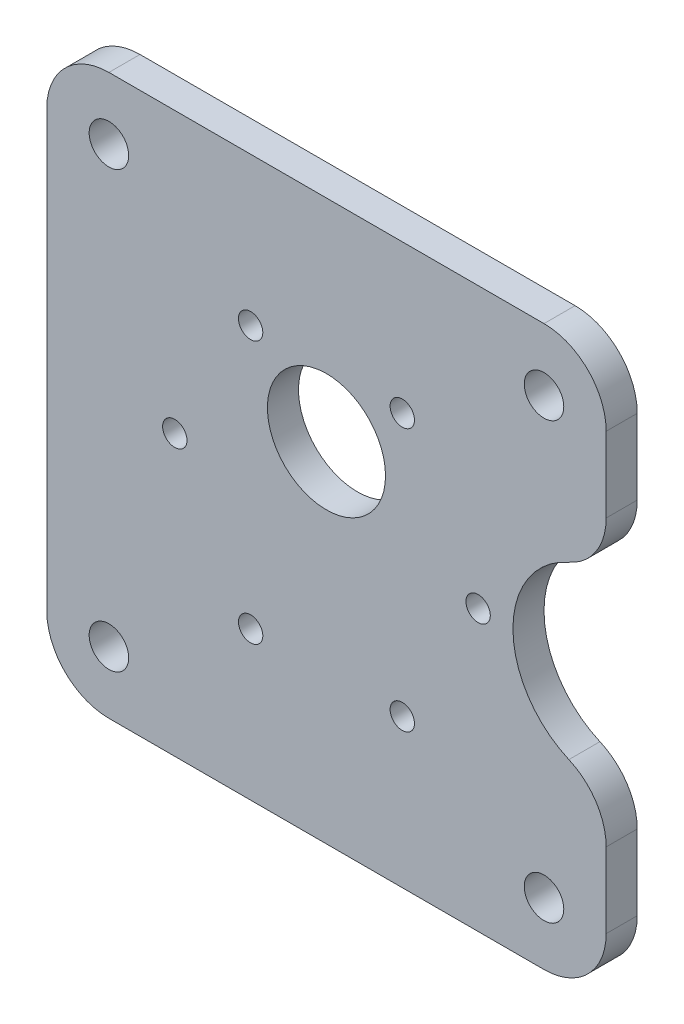
SolidWorks part; units mm, degrees
material "6061 Alloy"
ref_plane "Front Plane" through (0, 0, 0) normal (0, 0, 1) x (1, 0, 0)
ref_plane "Top Plane" through (0, 0, 0) normal (0, 1, 0) x (1, 0, 0)
ref_plane "Right Plane" through (0, 0, 0) normal (1, 0, 0) x (0, 0, -1)
sketch "Sketch1" plane through (0, 0, 0) normal (0, 0, 1) x (1, 0, 0)
  line L0 (0, 0) -> (-15.494, 0) construction
  line L1 (0, 0) -> (-7.747, 13.4182) construction
  line L3 (-28.575, 28.575) -> (28.575, 28.575)
  line L4 (-28.575, 28.575) -> (-28.575, -28.575)
  line L5 (-28.575, -28.575) -> (28.575, -28.575)
  line L6 (28.575, 28.575) -> (28.575, -28.575)
  line L7 (-28.575, 28.575) -> (28.575, -28.575) construction
  line L8 (-28.575, -28.575) -> (28.575, 28.575) construction
  line L9 (22.225, -22.225) -> (-22.225, -22.225) construction
  line L10 (22.225, -22.225) -> (22.225, 22.225) construction
  line L11 (22.225, 22.225) -> (-22.225, 22.225) construction
  line L12 (-22.225, -22.225) -> (-22.225, 22.225) construction
  line L13 (22.225, -22.225) -> (-22.225, 22.225) construction
  line L14 (22.225, 22.225) -> (-22.225, -22.225) construction
  circle A0 centre (0, 0) radius 15.494 construction
  circle A1 centre (-15.494, 0) radius 1.2446
  circle A2 centre (-7.747, 13.4182) radius 1.2446
  circle A3 centre (7.747, 13.4182) radius 1.2446
  circle A4 centre (15.494, 0) radius 1.2446
  circle A5 centre (7.747, -13.4182) radius 1.2446
  circle A6 centre (-7.747, -13.4182) radius 1.2446
  circle A7 centre (0, 7.0104) radius 6.0325
  circle A8 centre (-22.225, 22.225) radius 6.35 construction
  circle A9 centre (-22.225, -22.225) radius 6.35 construction
  circle A10 centre (22.225, -22.225) radius 6.35 construction
  circle A11 centre (22.225, 22.225) radius 6.35 construction
  circle A12 centre (-22.225, 22.225) radius 2.0193
  circle A13 centre (22.225, 22.225) radius 2.0193
  circle A14 centre (-22.225, -22.225) radius 2.0193
  circle A15 centre (22.225, -22.225) radius 2.0193
  arc A16 (28.575, 9.525) -> (28.575, -9.525) centre (28.575, 0) ccw
  point P38 (28.575, 0)
  dimension "D1" = 30.988
  dimension "D2" = 2.4892
  dimension "D3" = 6
  dimension "D4" = 60
  dimension "D6" = 12.065
  dimension "D10" = 12.7
  dimension "D11" = 4.0386
  dimension "D12" = 9.525
  dimension "D5" = 15.494
  dimension "D7" = 7.0104
  dimension "D8" = 57.15
  dimension "D9" = 57.15
extrude "Boss-Extrude1" add sketch "Sketch1" along normal mid plane 3.175
fillet "Fillet2" radius 6.35 6 edges at (-28.575, -28.575, 0) (28.575, -28.575, 0) (28.575, 28.575, 0) (-28.575, 28.575, 0) (28.575, 9.525, 0) (28.575, -9.525, 0)
sketch "Sketch2" plane through (0, 0, 1.5875) normal (0, 0, 1) x (1, 0, 0)
  line L0 (-1000, -28.575) -> (49000, -28.575) construction
  line L1 (-22.225, -28.575) -> (22.225, -28.575) construction
  line L2 (28.575, -981.6127) -> (28.575, 49018.3873) construction
  line L3 (28.575, 22.225) -> (28.575, 14.5497) construction
  line L4 (-1001.131, 28.575) -> (48998.869, 28.575) construction
  point P5 (0, -28.575)
  point P6 (28.575, -28.575)
  point P10 (28.575, 18.3873)
  point P12 (28.575, 28.575)
